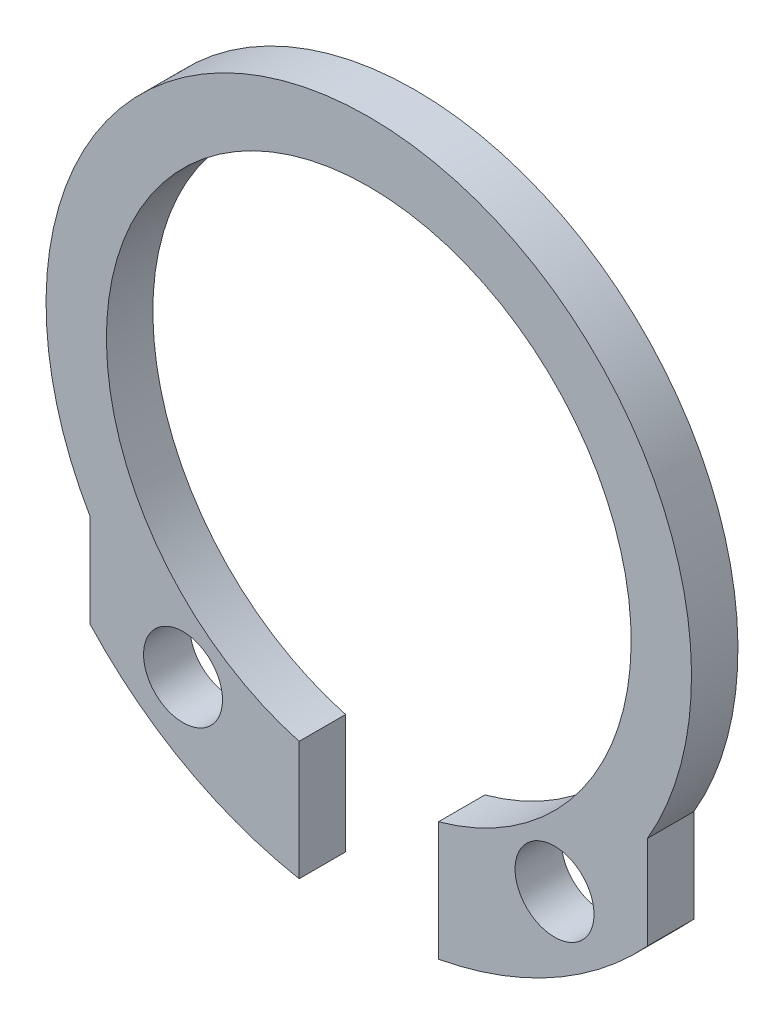
SolidWorks part; units mm, degrees
ref_plane "前视基准面" through (0, 0, 0) normal (0, 0, 1) x (1, 0, 0)
ref_plane "上视基准面" through (0, 0, 0) normal (0, 1, 0) x (1, 0, 0)
ref_plane "右视基准面" through (0, 0, 0) normal (1, 0, 0) x (0, 0, -1)
sketch "草图1" plane through (0, 0, 0) normal (0, 0, 1) x (1, 0, 0)
  line L0 (0, 0) -> (0, -9.258)
  line L1 (-1.5, -5.4472) -> (-1.5, -8.0108)
  line L2 (1.5, -5.4472) -> (1.5, -8.0108)
  line L3 (-6, -3.5075) -> (-6, -5.5157)
  line L4 (6, -3.5075) -> (6, -5.5157)
  arc A0 (1.5, -5.4472) -> (-1.5, -5.4472) centre (0, 0) ccw
  arc A1 (1.5, -8.0108) -> (6, -5.5157) centre (0, 0) ccw
  arc A2 (-6, -5.5157) -> (-1.5, -8.0108) centre (0, 0) ccw
  arc A3 (6, -3.5075) -> (-6, -3.5075) centre (0, 0) ccw
  circle A4 centre (-4, -5.5) radius 0.85
  circle A5 centre (4, -5.5) radius 0.85
  dimension "D1" = 11.3
  dimension "D2" = 1.7
  dimension "D3" = 16.3
  dimension "D8" = 1.7
  dimension "D11" = 6.95
  dimension "D12" = 5.5
  dimension "D4" = 1.5
  dimension "D5" = 3
  dimension "D6" = 6
  dimension "D7" = 12
  dimension "D9" = 4
  dimension "D10" = 4
extrude "凸台-拉伸1" add sketch "草图1" along normal blind 1 contours L4 A3 L3 A2 L1 A0 L2 A1 A5 A4
